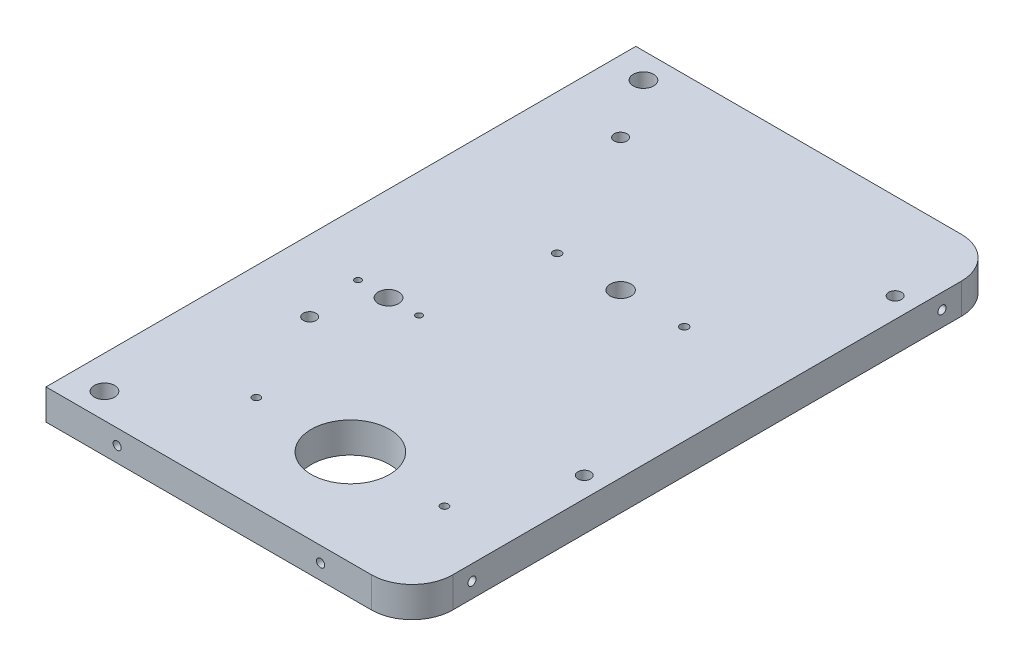
SolidWorks part; units mm, degrees
ref_plane "Спереди" through (0, 0, 0) normal (0, 0, 1) x (1, 0, 0)
ref_plane "Сверху" through (0, 0, 0) normal (0, 1, 0) x (1, 0, 0)
ref_plane "Справа" through (0, 0, 0) normal (1, 0, 0) x (0, 0, -1)
sketch "Эскиз1" plane through (0, 0, 0) normal (0, 1, 0) x (1, 0, 0)
  line L1 (-10, -22) -> (10, -22)
  line L2 (-10, -22) -> (-10, 22)
  line L3 (-10, 22) -> (10, 22)
  line L4 (10, -22) -> (10, 22)
extrude "Бобышка-Вытянуть1" add sketch "Эскиз1" along normal blind 3 contours L2 L1 L4 L3
sketch "Эскиз2" plane through (0, 3, 0) normal (0, 1, 0) x (1, 0, 0)
  circle A1 centre (6, -15) radius 0.8
  circle A2 centre (-6, -15) radius 0.8
extrude "Вырез-Вытянуть1" cut sketch "Эскиз2" against normal blind 3
sketch "Эскиз3" plane through (0, 0, 0) normal (0, -1, 0) x (1, 0, 0)
  line L0 (0, 0) -> (0, 13.3843)
  line L1 (10, 22) -> (31, 22)
  line L2 (10, 22) -> (10, -22)
  line L3 (10, -22) -> (31, -22)
  line L4 (31, 22) -> (31, -22)
  line L5 (-10, -22) -> (-31, -22)
  line L6 (-31, 22) -> (-31, -22)
  line L7 (-10, 22) -> (-31, 22)
  line L8 (-10, 22) -> (-10, -22)
  line M11 (10, -22) -> (10, 22)
  line M13 (-10, 22) -> (-10, -22)
extrude "Бобышка-Вытянуть3" add sketch "Эскиз3" against normal blind 3 contours L4 L1 L3 M11 | L7 L6 L5 M13
sketch "Эскиз4" plane through (0, 0, 0) normal (0, -1, 0) x (-1, 0, 0)
  line L1 (-31, 22) -> (31, 22)
  line L2 (-31, 22) -> (-31, 47)
  line L3 (-31, 47) -> (31, 47)
  line L4 (31, 22) -> (31, 47)
extrude "Бобышка-Вытянуть4" add sketch "Эскиз4" against normal blind 3 contours L2 L1 L4 L3
sketch "Эскиз5" plane through (0, 0, 0) normal (0, -1, 0) x (1, 0, 0)
  line L0 (6, 15) -> (-6.0031, 15)
  line L1 (-0.0015, 15) -> (-0.0015, -18)
  line L2 (22.4985, -18) -> (-22.5015, -18)
  line L3 (-0.0015, -18) -> (-0.0015, -44.0022)
  line L4 (-31.0031, -47) -> (-31.0031, -44.0022)
  line L5 (31, -47) -> (-31.0031, -47)
  line L6 (31, -47) -> (31, -44.0022)
  line L7 (31, -44.0022) -> (-31.0031, -44.0022)
  circle A0 centre (22.4985, -18) radius 2
  circle A1 centre (-22.5015, -18) radius 2
  circle A2 centre (-21.232, 6.1394) radius 0.25
  circle A3 centre (-23.1329, 7.2416) radius 0.25
  circle A4 centre (-23.1329, 5.0372) radius 0.25
  circle A5 centre (1.5588, -18) radius 0.225
  circle A6 centre (-3.5212, -18) radius 0.225
extrude "Вырез-Вытянуть2" cut sketch "Эскиз5" against normal blind 3 contours L7 L4 L5 L6 | A0 | A1
sketch "Эскиз6" plane through (0, 0, 0) normal (0, -1, 0) x (1, 0, 0)
  line L0 (31, -64.0022) -> (-31, -64.0022)
  line L1 (31, 22) -> (-31, 22)
  line L2 (31, 22) -> (31, 42)
  line L3 (31, 42) -> (-31, 42)
  line L4 (-31, 22) -> (-31, 42)
  line L5 (31, -64.0022) -> (31, -44.0022)
  line L6 (31, -44.0022) -> (-31, -44.0022)
  line L7 (-31, -64.0022) -> (-31, -44.0022)
extrude "Бобышка-Вытянуть5" add sketch "Эскиз6" against normal blind 3
sketch "Эскиз7" plane through (0, 3, 0) normal (0, 1, 0) x (1, 0, 0)
  line L0 (22.4985, 18) -> (-22.5015, 18)
  circle A1 centre (-16.5015, -6.1398) radius 0.8
  circle A2 centre (-28.5015, -6.1398) radius 0.8
  circle A3 centre (-21.232, -6.1394) radius 0.25
  circle A4 centre (-23.1329, -5.0372) radius 0.25
  circle A6 centre (-23.1329, -7.2416) radius 0.25
extrude "Вырез-Вытянуть4" cut sketch "Эскиз7" against normal blind 3 contours A1 | A3 | A6 | A4 | A2
sketch "Эскиз8" plane through (0, 3, 0) normal (0, 1, 0) x (1, 0, 0)
  circle A0 centre (6, -15) radius 0.8
  circle A4 centre (-6, -15) radius 0.8
extrude "Бобышка-Вытянуть6" add sketch "Эскиз8" against normal blind 3
sketch "Эскиз14" plane through (0, 3, 0) normal (0, 1, 0) x (1, 0, 0)
  line L0 (22.4985, 18) -> (-22.5015, 18)
  line L1 (-0.0015, -7) -> (-0.0015, -35)
  line L4 (-0.0015, -35) -> (-31, -35)
  line L6 (-0.0015, -42) -> (-31, -42)
  line L7 (-31, -35) -> (-31, -42)
  line L8 (-0.0015, -35) -> (31, -35)
  line L10 (-0.0015, -42) -> (31, -42)
  line L11 (31, -35) -> (31, -42)
  circle A0 centre (-0.0015, 18) radius 25
extrude "Вырез-Вытянуть5" cut sketch "Эскиз14" against normal blind 3 contours L4 L7 L6 L10 L11 L8
sketch "Эскиз15" plane through (0, 3, 0) normal (0, 1, 0) x (1, 0, 0)
  line L3 (31, -35) -> (31, 64.0022) construction
  line L8 (-0.0015, 48) -> (31, 48)
  line L11 (-0.0015, 64.0022) -> (31, 64.0022)
  line L12 (31, 48) -> (31, 64.0022)
  line L13 (-31, 64.0022) -> (31, 64.0022) construction
  line L15 (-0.0015, 48) -> (-31, 48)
  line L17 (-0.0015, 64.0022) -> (-31, 64.0022)
  line L18 (-31, 48) -> (-31, 64.0022)
  circle A0 centre (-27, -31) radius 1.5
  circle A2 centre (27, -31) radius 1.5
  circle A5 centre (27, 44) radius 1.5
  circle A6 centre (-27, 44) radius 1.5
extrude "Вырез-Вытянуть6" cut sketch "Эскиз15" against normal blind 3
sketch "Эскиз24" plane through (0, 0, 0) normal (0, -1, 0) x (1, 0, 0)
  line L1 (31, -48) -> (-31, -48)
  line L2 (31, -48) -> (31, -61)
  line L3 (31, -61) -> (-31, -61)
  line L4 (-31, -48) -> (-31, -61)
extrude "Бобышка-Вытянуть7" add sketch "Эскиз24" against normal blind 3 contours L2 L1 L4 L3
sketch "Эскиз25" plane through (0, 3, 0) normal (0, 1, 0) x (1, 0, 0)
  line L1 (-31, -35) -> (31, -35)
  line L2 (-31, -35) -> (-31, -50)
  line L3 (-31, -50) -> (31, -50)
  line L4 (31, -35) -> (31, -50)
  circle A2 centre (27, -46) radius 1.5
  circle A3 centre (-27, -46) radius 1.5
extrude "Бобышка-Вытянуть8" add sketch "Эскиз25" against normal blind 3
sketch "Эскиз26" plane through (0, 3, 0) normal (0, 1, 0) x (1, 0, 0)
  circle A3 centre (-27, -17.1398) radius 1.5
  circle A4 centre (27, -17.1398) radius 1.5
extrude "Вырез-Вытянуть7" cut sketch "Эскиз26" against normal blind 3
cosmetic thread "Условное изображение резьбы2"
cosmetic thread "Условное изображение резьбы3"
sketch "Эскиз31" plane through (0, 3, 0) normal (0, 1, 0) x (1, 0, 0)
  circle A0 centre (-27, -31) radius 1.5
  circle A1 centre (27, -31) radius 1.5
  circle A2 centre (27, -46) radius 1.5
  circle A3 centre (-27, -46) radius 1.5
extrude "Бобышка-Вытянуть10" add sketch "Эскиз31" against normal blind 3
sketch "Эскиз36" plane through (0, 0, 0) normal (0, -1, 0) x (1, 0, 0)
  circle A0 centre (0, 36.1398) radius 7.7
extrude "Вырез-Вытянуть12" cut sketch "Эскиз36" against normal blind 3 contours A0
sketch "Эскиз45" plane through (0, 3, 0) normal (0, 1, 0) x (1, 0, 0)
  circle A0 centre (18.5, -36.1398) radius 1.05
  circle A1 centre (-18.5, -36.1398) radius 1.05
extrude "Вырез-Вытянуть13" cut sketch "Эскиз45" against normal blind 3
sketch "Эскиз50" plane through (0, 3, 0) normal (0, 1, 0) x (1, 0, 0)
  circle A0 centre (26, 54.5) radius 2
  circle A1 centre (-26, 54.5) radius 2
extrude "Вырез-Вытянуть14" cut sketch "Эскиз50" against normal blind 3
sketch "Эскиз51" plane through (0, 0, 0) normal (0, -1, 0) x (-1, 0, 0)
  circle A0 centre (26, 54.5) radius 2
  circle A1 centre (-26, 54.5) radius 2
extrude "Бобышка-Вытянуть11" add sketch "Эскиз51" against normal blind 3
sketch "Эскиз52" plane through (0, 0, 0) normal (0, -1, 0) x (1, 0, 0)
  line L1 (-31, 50) -> (31, 50)
  line L2 (-31, 50) -> (-31, 55)
  line L3 (-31, 55) -> (31, 55)
  line L4 (31, 50) -> (31, 55)
extrude "Бобышка-Вытянуть12" add sketch "Эскиз52" against normal blind 3 contours L2 L1 L4 L3
sketch "Эскиз53" plane through (0, 0, 0) normal (0, -1, 0) x (1, 0, 0)
  line L1 (-31, 55) -> (-41, 55)
  line L2 (-31, 55) -> (-31, -61)
  line L3 (-31, -61) -> (-41, -61)
  line L4 (-41, 55) -> (-41, -61)
extrude "Бобышка-Вытянуть13" add sketch "Эскиз53" against normal blind 3
sketch "Эскиз54" plane through (0, 0, 0) normal (0, -1, 0) x (1, 0, 0)
  circle A0 centre (-34.5, 50) radius 2
  circle A1 centre (-34.5, -56) radius 2
extrude "Вырез-Вытянуть15" cut sketch "Эскиз54" against normal blind 10
sketch "Эскиз55" plane through (0, 0, 0) normal (0, -1, 0) x (-1, 0, 0)
  line L5 (-31, 61) -> (-23, 61)
  line L6 (-31, 61) -> (-31, 53)
  line L10 (-31, -55) -> (-23, -55)
  line L11 (-31, -55) -> (-31, -47)
  arc A2 (-23, 61) -> (-31, 53) centre (-23, 53) ccw
  arc A3 (-23, -55) -> (-31, -47) centre (-23, -47) cw
extrude "Вырез-Вытянуть17" cut sketch "Эскиз55" against normal blind 7
sketch "Эскиз57" plane through (0, 0, 0) normal (0, -1, 0) x (1, 0, 0)
  line L1 (-41, 55) -> (23, 55)
  line L2 (-41, 55) -> (-41, -61)
  line L3 (-41, -61) -> (23, -61)
  line L4 (31, 47) -> (31, -53)
  arc A0 (23, -61) -> (31, -53) centre (23, -53) ccw
  arc A1 (23, 55) -> (31, 47) centre (23, 47) cw
  circle A2 centre (0, 36.1398) radius 7.7
  circle A3 centre (27, 17.1398) radius 1.5
  circle A4 centre (-27, 17.1398) radius 1.5
  circle A5 centre (-22.5015, -18) radius 2
  circle A6 centre (22.4985, -18) radius 2
  circle A7 centre (-27, -44) radius 1.5
  circle A8 centre (27, -44) radius 1.5
  circle A9 centre (-34.5, -56) radius 2
  circle A10 centre (-34.5, 50) radius 2
  circle A11 centre (-18.5, 36.1398) radius 1.05
  circle A12 centre (18.5, 36.1398) radius 1.05
  circle A13 centre (-16.5015, 6.1398) radius 0.8
  circle A14 centre (-28.5015, 6.1398) radius 0.8
  circle A15 centre (-23.1329, 7.2416) radius 0.25
  circle A16 centre (-21.232, 6.1394) radius 0.25
  circle A17 centre (-23.1329, 5.0372) radius 0.25
  circle A18 centre (-3.5212, -18) radius 0.225
  circle A19 centre (1.5588, -18) radius 0.225
  dimension "D1" = 8
extrude "Бобышка-Вытянуть14" add sketch "Эскиз57" along normal blind 3
sketch "Эскиз58" plane through (31, 0, 0) normal (1, 0, 0) x (0, 0, -1)
  circle A0 centre (49.22, 0) radius 1
  circle A1 centre (-43.22, 0) radius 1
extrude "Вырез-Вытянуть18" cut sketch "Эскиз58" against normal blind 6
sketch "Эскиз59" plane through (0, 0, 55) normal (0, 0, 1) x (1, 0, 0)
  circle A0 centre (13, 0) radius 1
  circle A1 centre (-27, 0) radius 1
extrude "Вырез-Вытянуть19" cut sketch "Эскиз59" against normal blind 6
sketch "Эскиз60" plane through (0, 0, -61) normal (0, 0, -1) x (-1, 0, 0)
  circle A0 centre (27, 0) radius 1
  circle A1 centre (-13, 0) radius 1
extrude "Вырез-Вытянуть20" cut sketch "Эскиз60" against normal blind 6
sketch "Эскиз61" plane through (0, -3, 0) normal (0, -1, 0) x (1, 0, 0)
  circle A0 centre (-22.502, 6.1394) radius 3
extrude "Вырез-Вытянуть21" cut sketch "Эскиз61" against normal blind 3
sketch "Эскиз62" plane through (0, 0, 0) normal (0, -1, 0) x (1, 0, 0)
  circle A0 centre (-22.502, 6.1394) radius 2
extrude "Вырез-Вытянуть22" cut sketch "Эскиз62" against normal blind 3
sketch "Эскиз63" plane through (0, -3, 0) normal (0, -1, 0) x (1, 0, 0)
  circle A0 centre (-0.9812, -18) radius 2.55
extrude "Вырез-Вытянуть23" cut sketch "Эскиз63" against normal blind 3
sketch "Эскиз64" plane through (0, 0, 0) normal (0, -1, 0) x (1, 0, 0)
  circle A0 centre (-0.9812, -18) radius 2.05
extrude "Вырез-Вытянуть24" cut sketch "Эскиз64" against normal blind 3
sketch "Эскиз65" plane through (0, -3, 0) normal (0, -1, 0) x (-1, 0, 0)
  circle A0 centre (22.5015, 18) radius 2
  circle A1 centre (-22.4985, 18) radius 2
extrude "Бобышка-Вытянуть15" add sketch "Эскиз65" against normal blind 6
sketch "Эскиз66" plane through (0, -3, 0) normal (0, -1, 0) x (1, 0, 0)
  circle A0 centre (10.6048, -18) radius 1
  circle A1 centre (-12.5672, -18) radius 1
extrude "Вырез-Вытянуть25" cut sketch "Эскиз66" against normal blind 6
sketch "Эскиз67" plane through (0, -3, 0) normal (0, -1, 0) x (1, 0, 0)
  circle A0 centre (-0.9812, -18) radius 2.55
  circle A1 centre (-0.9812, -18) radius 2.9321
extrude "Бобышка-Вытянуть16" add sketch "Эскиз67" against normal blind 3
sketch "Эскиз68" plane through (0, -3, 0) normal (0, -1, 0) x (1, 0, 0)
  circle A0 centre (27, 17.1398) radius 1.25
  circle A1 centre (27, 17.1398) radius 1.5
  circle A2 centre (27, -44) radius 1.25
  circle A3 centre (27, -44) radius 1.5
  circle A4 centre (-27, 17.1398) radius 1.25
  circle A5 centre (-27, 17.1398) radius 1.5
  circle A8 centre (10.6048, -18) radius 1
  circle A9 centre (10.6048, -18) radius 0.75
  circle A10 centre (-12.5672, -18) radius 0.75
  circle A11 centre (-12.5672, -18) radius 1
  circle A12 centre (18.5, 36.1398) radius 1.05
  circle A13 centre (18.5, 36.1398) radius 0.75
  circle A14 centre (-18.5, 36.1398) radius 0.75
  circle A15 centre (-18.5, 36.1398) radius 1.05
  circle A16 centre (-27, -44) radius 1.6
  circle A17 centre (-27, -44) radius 1.25
extrude "Бобышка-Вытянуть17" add sketch "Эскиз68" against normal blind 6
cosmetic thread "Условное изображение резьбы5" parameters "D2"=2
cosmetic thread "Условное изображение резьбы6" parameters "D2"=2
cosmetic thread "Условное изображение резьбы9" parameters "D2"=3
cosmetic thread "Условное изображение резьбы10" parameters "D2"=3
cosmetic thread "Условное изображение резьбы11" parameters "D2"=3
cosmetic thread "Условное изображение резьбы12" parameters "D2"=3
sketch "Эскиз69" plane through (0, -3, 0) normal (0, -1, 0) x (1, 0, 0)
  circle A0 centre (-16.5015, 6.1398) radius 0.8
  circle A1 centre (-16.5015, 6.1398) radius 0.625
  circle A2 centre (-28.5024, 6.1398) radius 0.625
  circle A3 centre (-28.5024, 6.1398) radius 1
extrude "Бобышка-Вытянуть18" add sketch "Эскиз69" against normal blind 6
cosmetic thread "Условное изображение резьбы13" parameters "D2"=1.6
cosmetic thread "Условное изображение резьбы14" parameters "D2"=1.6
sketch "Эскиз70" plane through (0, 0, -61) normal (0, 0, -1) x (-1, 0, 0)
  circle A0 centre (-13, 0) radius 1
  circle A1 centre (-13, 0) radius 0.8
  circle A2 centre (27, 0) radius 1
  circle A3 centre (27, 0) radius 0.8
extrude "Бобышка-Вытянуть19" add sketch "Эскиз70" against normal blind 6
cosmetic thread "Условное изображение резьбы19" parameters "D2"=2
cosmetic thread "Условное изображение резьбы20" parameters "D2"=2
sketch "Эскиз71" plane through (31, 0, 0) normal (1, 0, 0) x (0, 0, -1)
  circle A0 centre (-43.22, 0) radius 1
  circle A1 centre (-43.22, 0) radius 0.8
  circle A2 centre (49.22, 0) radius 1
  circle A3 centre (49.22, 0) radius 0.8
extrude "Бобышка-Вытянуть20" add sketch "Эскиз71" against normal blind 6
cosmetic thread "Условное изображение резьбы17" parameters "D1"=5, "D2"=2
cosmetic thread "Условное изображение резьбы18" parameters "D2"=2
sketch "Эскиз72" plane through (0, 0, 55) normal (0, 0, 1) x (1, 0, 0)
  circle A0 centre (-27, 0) radius 1
  circle A1 centre (-27, 0) radius 0.8
  circle A2 centre (13, 0) radius 1
  circle A3 centre (13, 0) radius 0.8
extrude "Бобышка-Вытянуть21" add sketch "Эскиз72" against normal blind 6
cosmetic thread "Условное изображение резьбы15" parameters "D2"=2
cosmetic thread "Условное изображение резьбы16" parameters "D2"=2
sketch "Эскиз73" plane through (0, -3, 0) normal (0, -1, 0) x (1, 0, 0)
  circle A0 centre (-12.5672, -18) radius 0.9474
  circle A1 centre (10.6048, -18) radius 0.9602
extrude "Бобышка-Вытянуть22" add sketch "Эскиз73" against normal blind 6
sketch "Эскиз74" plane through (0, -3, 0) normal (0, -1, 0) x (1, 0, 0)
  circle A0 centre (-13.4812, -18) radius 0.8
  circle A1 centre (11.5188, -18) radius 0.8
extrude "Вырез-Вытянуть26" cut sketch "Эскиз74" against normal blind 6
cosmetic thread "Условное изображение резьбы21" parameters "D1"=6, "D2"=2
cosmetic thread "Условное изображение резьбы22" parameters "D1"=6, "D2"=2
